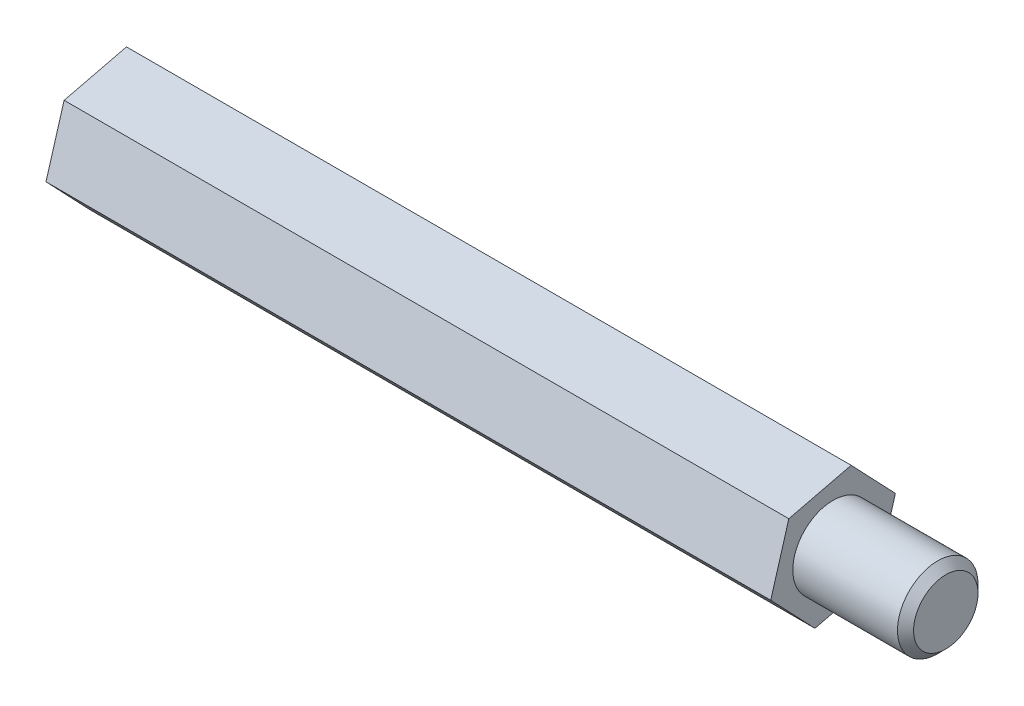
SolidWorks part; units mm, degrees
material "黄铜"
ref_plane "前视基准面" through (0, 0, 0) normal (0, 0, 1) x (1, 0, 0)
ref_plane "上视基准面" through (0, 0, 0) normal (0, 1, 0) x (1, 0, 0)
ref_plane "右视基准面" through (0, 0, 0) normal (1, 0, 0) x (0, 0, -1)
sketch "草图1" plane through (0, 0, 0) normal (1, 0, 0) x (0, 0, -1)
  line L1 (2.7473, -2.8848) -> (3.872, 0.9368)
  line L2 (3.872, 0.9368) -> (1.1247, 3.8217)
  line L3 (1.1247, 3.8217) -> (-2.7473, 2.8848)
  line L4 (-2.7473, 2.8848) -> (-3.872, -0.9368)
  line L5 (-3.872, -0.9368) -> (-1.1247, -3.8217)
  line L6 (-1.1247, -3.8217) -> (2.7473, -2.8848)
  circle A0 centre (0, 0) radius 3.45 construction
  dimension "D1" = 6.9
extrude "凸台-拉伸1" add sketch "草图1" along normal blind 45
sketch "草图2" plane through (45, 0, 0) normal (1, 0, 0) x (0, 0, -1)
  circle A0 centre (0, 0) radius 2.5
  dimension "D1" = 5
extrude "凸台-拉伸2" add sketch "草图2" along normal blind 7
chamfer "倒角1" distance 0.5 angle 45 1 edges at (52, 0, -2.5)
sketch "草图3" plane through (0, 0, 0) normal (-1, 0, 0) x (0, 0, 1)
  circle A0 centre (0, 0) radius 2.5
  dimension "D1" = 5
extrude "切除-拉伸1" cut sketch "草图3" against normal blind 7
